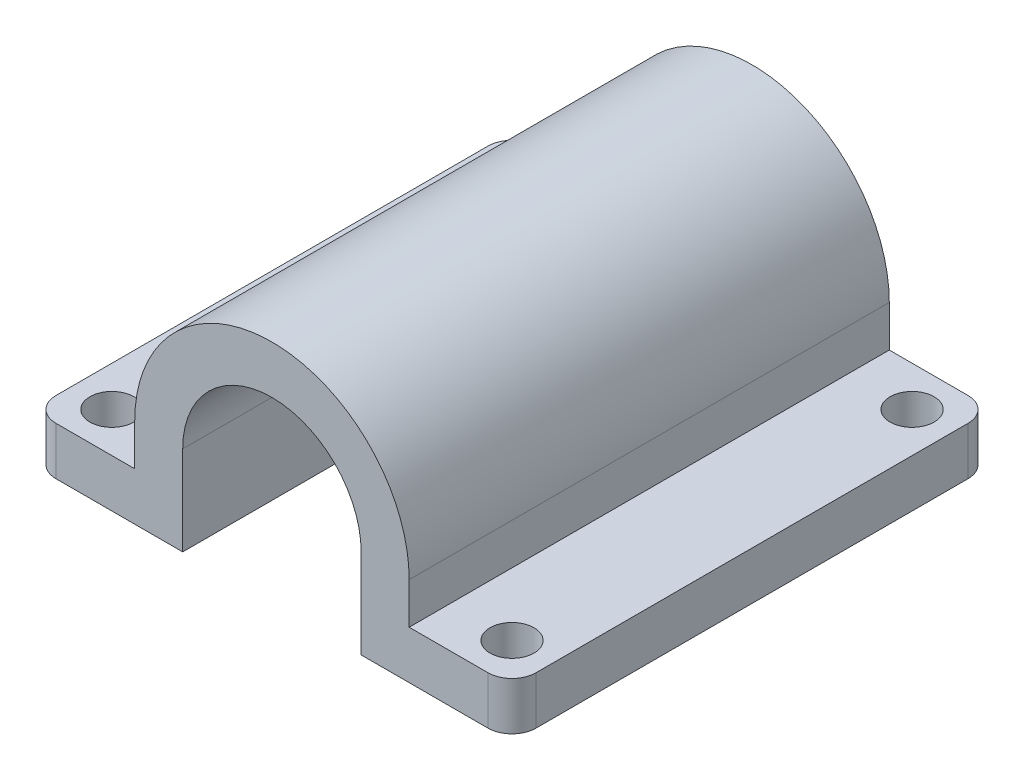
SolidWorks part; units mm, degrees
ref_plane "Front Plane" through (0, 0, 0) normal (0, 0, 1) x (1, 0, 0)
ref_plane "Top Plane" through (0, 0, 0) normal (0, 1, 0) x (1, 0, 0)
ref_plane "Right Plane" through (0, 0, 0) normal (1, 0, 0) x (0, 0, -1)
sketch "Sketch1" plane through (0, 0, 0) normal (0, 0, 1) x (1, 0, 0)
  line L0 (-11.15, 0) -> (-11.15, -11.15)
  line L2 (11.15, -11.15) -> (11.15, 0)
  line L4 (-30, -11.15) -> (-11.15, -11.15)
  line L5 (-30, -11.15) -> (-30, -5.15)
  line L6 (-30, -5.15) -> (-17.15, -5.15)
  line L7 (-17.15, -5.15) -> (-17.15, 0)
  line L8 (30, -11.15) -> (30, -5.15)
  line L9 (30, -5.15) -> (17.15, -5.15)
  line L10 (17.15, -5.15) -> (17.15, 0)
  line L11 (11.15, -11.15) -> (30, -11.15)
  arc A0 (11.15, 0) -> (-11.15, 0) centre (0, 0) ccw
  arc A1 (17.15, 0) -> (-17.15, 0) centre (0, 0) ccw
  point P14 (0, -11.15)
  dimension "D1" = 22.3
  dimension "D2" = 60
  dimension "D3" = 6
extrude "Boss-Extrude1" add sketch "Sketch1" along normal blind 60
sketch "Sketch2" plane through (0, -5.15, 0) normal (0, 1, 0) x (1, 0, 0)
  line L0 (-30, -30) -> (-17.15, -30) construction
  line L1 (-30, -60) -> (-30, 0) construction
  line L2 (-17.15, -60) -> (-17.15, 0) construction
  line L3 (0, 0) -> (0, -60) construction
  line L4 (-17.15, -60) -> (17.15, -60) construction
  line L5 (-17.15, 0) -> (-30, 0) construction
  circle A0 centre (-25, -5) radius 2.75
  circle A1 centre (-25, -55) radius 2.75
  circle A2 centre (25, -55) radius 2.75
  circle A3 centre (25, -5) radius 2.75
  dimension "D1" = 5.5
  dimension "D2" = 5
  dimension "D3" = 5
extrude "Cut-Extrude1" cut sketch "Sketch2" against normal blind 6
fillet "Fillet1" radius 3 4 edges at (30, -8.15, 0) (30, -8.15, 60) (-30, -8.15, 60) (-30, -8.15, 0)
